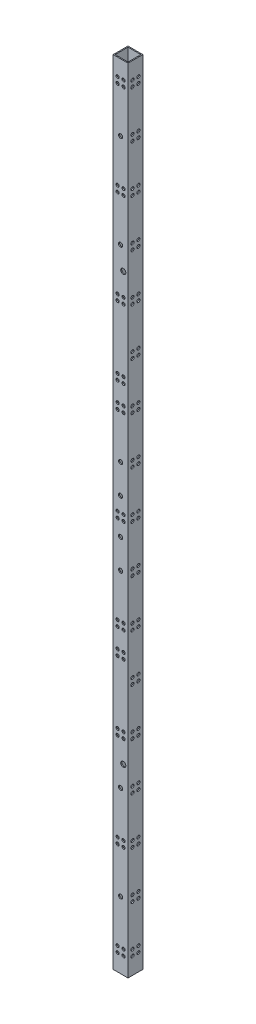
SolidWorks part; units mm, degrees
ref_plane "前视基准面" through (0, 0, 0) normal (0, 0, 1) x (1, 0, 0)
ref_plane "上视基准面" through (0, 0, 0) normal (0, 1, 0) x (1, 0, 0)
ref_plane "右视基准面" through (0, 0, 0) normal (1, 0, 0) x (0, 0, -1)
other "Configuration Table"
sketch "草图1" plane through (0, 0, 0) normal (0, 1, 0) x (1, 0, 0)
  line L1 (6.5, -6.5) -> (-6.5, -6.5)
  line L2 (6.5, -6.5) -> (6.5, 6.5)
  line L3 (6.5, 6.5) -> (-6.5, 6.5)
  line L4 (-6.5, -6.5) -> (-6.5, 6.5)
  line L5 (6.5, -6.5) -> (-6.5, 6.5) construction
  line L6 (6.5, 6.5) -> (-6.5, -6.5) construction
  line L7 (7.5, -7.5) -> (-7.5, -7.5)
  line L8 (7.5, -7.5) -> (7.5, 7.5)
  line L9 (7.5, 7.5) -> (-7.5, 7.5)
  line L10 (-7.5, -7.5) -> (-7.5, 7.5)
  line L11 (7.5, -7.5) -> (-7.5, 7.5) construction
  line L12 (7.5, 7.5) -> (-7.5, -7.5) construction
  point P0 (0, 0)
  point P6 (0, 0)
  dimension "D1" = 15
  dimension "D2" = 13
extrude "凸台-拉伸1" add sketch "草图1" along normal blind 800
sketch "草图2" plane through (0, 0, 7.5) normal (0, 0, 1) x (1, 0, 0)
  line L0 (0, 804.3358) -> (0, 762.8538) construction
  line L1 (-7.5, 780) -> (7.5, 780) construction
  line L2 (-7.5, 800) -> (-7.5, 0) construction
  line L3 (7.5, 800) -> (7.5, 0) construction
  line L4 (-7.5, 800) -> (7.5, 800) construction
  line L5 (-7.5, 400) -> (7.5, 400) construction
  line L6 (-7.5, 20) -> (7.5, 20) construction
  line L7 (-7.5, 615.5) -> (7.5, 615.5) construction
  line L8 (-7.5, 520.5) -> (7.5, 520.5) construction
  line L9 (-7.5, 279.5) -> (7.5, 279.5) construction
  circle A0 centre (-3, 783) radius 1.6
  circle A1 centre (3, 783) radius 1.6
  circle A2 centre (-3, 777) radius 1.6
  circle A3 centre (3, 777) radius 1.6
  circle A4 centre (3, 23) radius 1.6
  circle A5 centre (-3, 23) radius 1.6
  circle A6 centre (3, 17) radius 1.6
  circle A7 centre (-3, 17) radius 1.6
  circle A8 centre (0, 418) radius 2.1
  circle A9 centre (0, 382) radius 2.1
  circle A10 centre (3, 118) radius 1.6
  circle A11 centre (-3, 118) radius 1.6
  circle A12 centre (-3, 112) radius 1.6
  circle A13 centre (3, 112) radius 1.6
  circle A14 centre (3, 213) radius 1.6
  circle A15 centre (-3, 213) radius 1.6
  circle A16 centre (-3, 207) radius 1.6
  circle A17 centre (3, 207) radius 1.6
  circle A18 centre (3, 308) radius 1.6
  circle A19 centre (-3, 308) radius 1.6
  circle A20 centre (-3, 302) radius 1.6
  circle A21 centre (3, 302) radius 1.6
  circle A22 centre (3, 403) radius 1.6
  circle A23 centre (-3, 403) radius 1.6
  circle A24 centre (-3, 397) radius 1.6
  circle A25 centre (3, 397) radius 1.6
  circle A26 centre (3, 498) radius 1.6
  circle A27 centre (-3, 498) radius 1.6
  circle A28 centre (-3, 492) radius 1.6
  circle A29 centre (3, 492) radius 1.6
  circle A30 centre (3, 593) radius 1.6
  circle A31 centre (-3, 593) radius 1.6
  circle A32 centre (-3, 587) radius 1.6
  circle A33 centre (3, 587) radius 1.6
  circle A34 centre (3, 688) radius 1.6
  circle A35 centre (-3, 688) radius 1.6
  circle A36 centre (-3, 682) radius 1.6
  circle A37 centre (3, 682) radius 1.6
  circle A38 centre (0, 732.5) radius 2.1
  circle A39 centre (0, 637.5) radius 2.1
  circle A41 centre (0, 447.5) radius 2.1
  circle A42 centre (0, 352.5) radius 2.1
  circle A44 centre (0, 162.5) radius 2.1
  circle A45 centre (0, 67.5) radius 2.1
  circle A46 centre (2.75, 615.5) radius 2.6
  circle A47 centre (-3, 523.5) radius 1.6
  circle A48 centre (3, 523.5) radius 1.6
  circle A49 centre (3, 517.5) radius 1.6
  circle A50 centre (-3, 517.5) radius 1.6
  circle A51 centre (0, 542.5) radius 2.1 [skipped]
  circle A52 centre (-3, 282.5) radius 1.6
  circle A53 centre (3, 282.5) radius 1.6
  circle A54 centre (3, 276.5) radius 1.6
  circle A55 centre (-3, 276.5) radius 1.6
  circle A56 centre (2.75, 184.5) radius 2.6
  circle A57 centre (0, 257.5) radius 2.1 [skipped]
  point P98 (0, 0)
  point P99 (0, 0)
  dimension "D2" = 3.2
  dimension "D5" = 4.2
  dimension "D8" = 4.2
  dimension "D12" = 5.2
  dimension "D14" = 3.2
  dimension "D1" = 20
  dimension "D3" = 6
  dimension "D4" = 6
  dimension "D6" = 36
  dimension "D9" = 47.5
  dimension "D11" = 184.5
  dimension "D13" = 4.75
  dimension "D15" = 6
  dimension "D16" = 6
  dimension "D17" = 259.5
  dimension "D7" = 8
  dimension "D10" = 8
extrude "切除-拉伸1" cut sketch "草图2" against normal up to surface (15 mm away) up to face at (0, 400, -7.5)
sketch "草图3" plane through (-7.5, 0, 0) normal (-1, 0, 0) x (0, 0, 1)
  line L0 (0, 809.7886) -> (0, 782.9032) construction
  line L1 (-7.5, 780) -> (7.5, 780) construction
  line L2 (-7.5, 800) -> (-7.5, 0) construction
  line L3 (7.5, 800) -> (7.5, 0) construction
  line L4 (-7.5, 800) -> (7.5, 800) construction
  circle A0 centre (-3, 783) radius 1.6
  circle A1 centre (3, 783) radius 1.6
  circle A2 centre (-3, 777) radius 1.6
  circle A3 centre (3, 777) radius 1.6
  circle A4 centre (-3, 735.5) radius 1.6
  circle A5 centre (-3, 729.5) radius 1.6
  circle A6 centre (3, 729.5) radius 1.6
  circle A7 centre (3, 735.5) radius 1.6
  circle A8 centre (-3, 688) radius 1.6
  circle A9 centre (-3, 682) radius 1.6
  circle A10 centre (3, 682) radius 1.6
  circle A11 centre (3, 688) radius 1.6
  circle A12 centre (-3, 640.5) radius 1.6
  circle A13 centre (-3, 634.5) radius 1.6
  circle A14 centre (3, 634.5) radius 1.6
  circle A15 centre (3, 640.5) radius 1.6
  circle A16 centre (-3, 593) radius 1.6
  circle A17 centre (-3, 587) radius 1.6
  circle A18 centre (3, 587) radius 1.6
  circle A19 centre (3, 593) radius 1.6
  circle A20 centre (-3, 545.5) radius 1.6
  circle A21 centre (-3, 539.5) radius 1.6
  circle A22 centre (3, 539.5) radius 1.6
  circle A23 centre (3, 545.5) radius 1.6
  circle A24 centre (-3, 498) radius 1.6
  circle A25 centre (-3, 492) radius 1.6
  circle A26 centre (3, 492) radius 1.6
  circle A27 centre (3, 498) radius 1.6
  circle A28 centre (-3, 450.5) radius 1.6
  circle A29 centre (-3, 444.5) radius 1.6
  circle A30 centre (3, 444.5) radius 1.6
  circle A31 centre (3, 450.5) radius 1.6
  circle A32 centre (-3, 403) radius 1.6
  circle A33 centre (-3, 397) radius 1.6
  circle A34 centre (3, 397) radius 1.6
  circle A35 centre (3, 403) radius 1.6
  circle A36 centre (-3, 355.5) radius 1.6
  circle A37 centre (-3, 349.5) radius 1.6
  circle A38 centre (3, 349.5) radius 1.6
  circle A39 centre (3, 355.5) radius 1.6
  circle A40 centre (-3, 308) radius 1.6
  circle A41 centre (-3, 302) radius 1.6
  circle A42 centre (3, 302) radius 1.6
  circle A43 centre (3, 308) radius 1.6
  circle A44 centre (-3, 260.5) radius 1.6
  circle A45 centre (-3, 254.5) radius 1.6
  circle A46 centre (3, 254.5) radius 1.6
  circle A47 centre (3, 260.5) radius 1.6
  circle A48 centre (-3, 213) radius 1.6
  circle A49 centre (-3, 207) radius 1.6
  circle A50 centre (3, 207) radius 1.6
  circle A51 centre (3, 213) radius 1.6
  circle A52 centre (-3, 165.5) radius 1.6
  circle A53 centre (-3, 159.5) radius 1.6
  circle A54 centre (3, 159.5) radius 1.6
  circle A55 centre (3, 165.5) radius 1.6
  circle A56 centre (-3, 118) radius 1.6
  circle A57 centre (-3, 112) radius 1.6
  circle A58 centre (3, 112) radius 1.6
  circle A59 centre (3, 118) radius 1.6
  circle A60 centre (-3, 70.5) radius 1.6
  circle A61 centre (-3, 64.5) radius 1.6
  circle A62 centre (3, 64.5) radius 1.6
  circle A63 centre (3, 70.5) radius 1.6
  circle A64 centre (-3, 23) radius 1.6
  circle A65 centre (-3, 17) radius 1.6
  circle A66 centre (3, 17) radius 1.6
  circle A67 centre (3, 23) radius 1.6
  dimension "D2" = 3.2
  dimension "D5" = 17
  dimension "D1" = 20
  dimension "D3" = 6
  dimension "D4" = 6
extrude "切除-拉伸2" cut sketch "草图3" against normal up to surface (15 mm away) up to face at (7.5, 400, 0)
